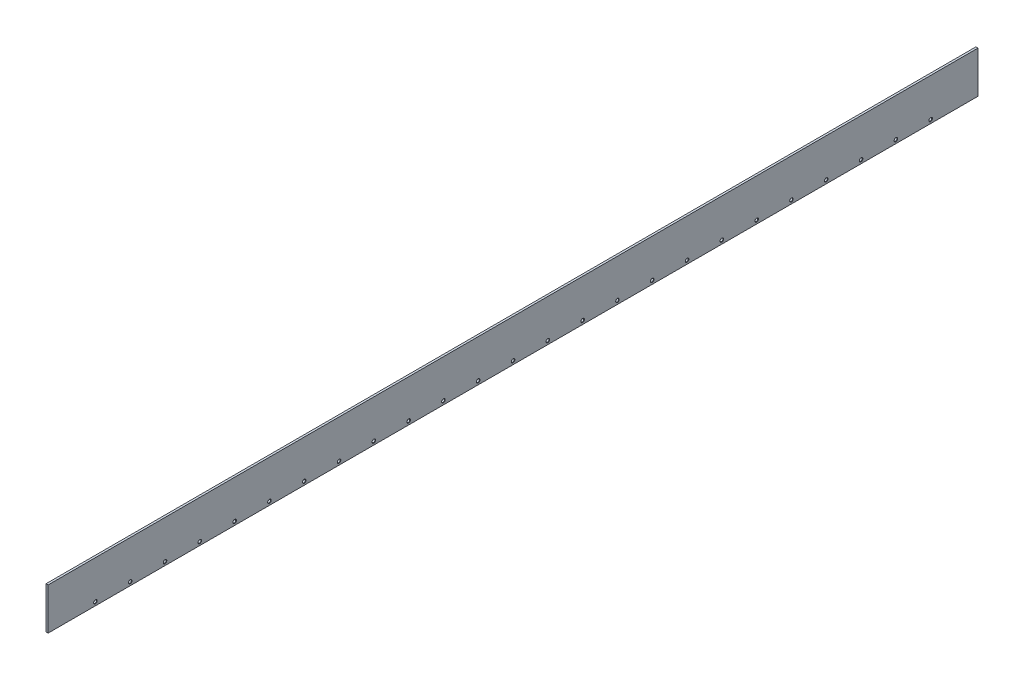
SolidWorks part; units mm, degrees
material "Plain Carbon Steel"
ref_plane "Front Plane" through (0, 0, 0) normal (0, 0, 1) x (1, 0, 0)
ref_plane "Top Plane" through (0, 0, 0) normal (0, 1, 0) x (1, 0, 0)
ref_plane "Right Plane" through (0, 0, 0) normal (1, 0, 0) x (0, 0, -1)
sketch "Sketch1" plane through (0, 0, 0) normal (0, 0, 1) x (1, 0, 0)
  line L1 (-1.5, -30) -> (1.5, -30)
  line L2 (-1.5, -30) -> (-1.5, 30)
  line L3 (-1.5, 30) -> (1.5, 30)
  line L4 (1.5, -30) -> (1.5, 30)
  line L5 (-1.5, -30) -> (1.5, 30) construction
  line L6 (-1.5, 30) -> (1.5, -30) construction
  point P0 (0, 0)
  dimension "D1" = 3
  dimension "D2" = 60
extrude "Boss-Extrude1" add sketch "Sketch1" along normal mid plane 1336
sketch "Sketch2" plane through (1.5, 0, 0) normal (1, 0, 0) x (0, 0, -1)
  line L0 (-668, -30) -> (668, -30) construction
  circle A0 centre (0, -25) radius 2.05
  dimension "D2" = 4.1
  dimension "D1" = 5
extrude "Cut-Extrude1" cut sketch "Sketch2" against normal blind 10
chamfer "Chamfer1" distance 0.5 angle 45 1 edges at (1.5, -25, -2.05)
pattern_linear "LPattern1" count 13 spacing 50 along (0, 0, -1) count 13 spacing 50 along (0, 0, 1) of "Chamfer1", "Cut-Extrude1"
